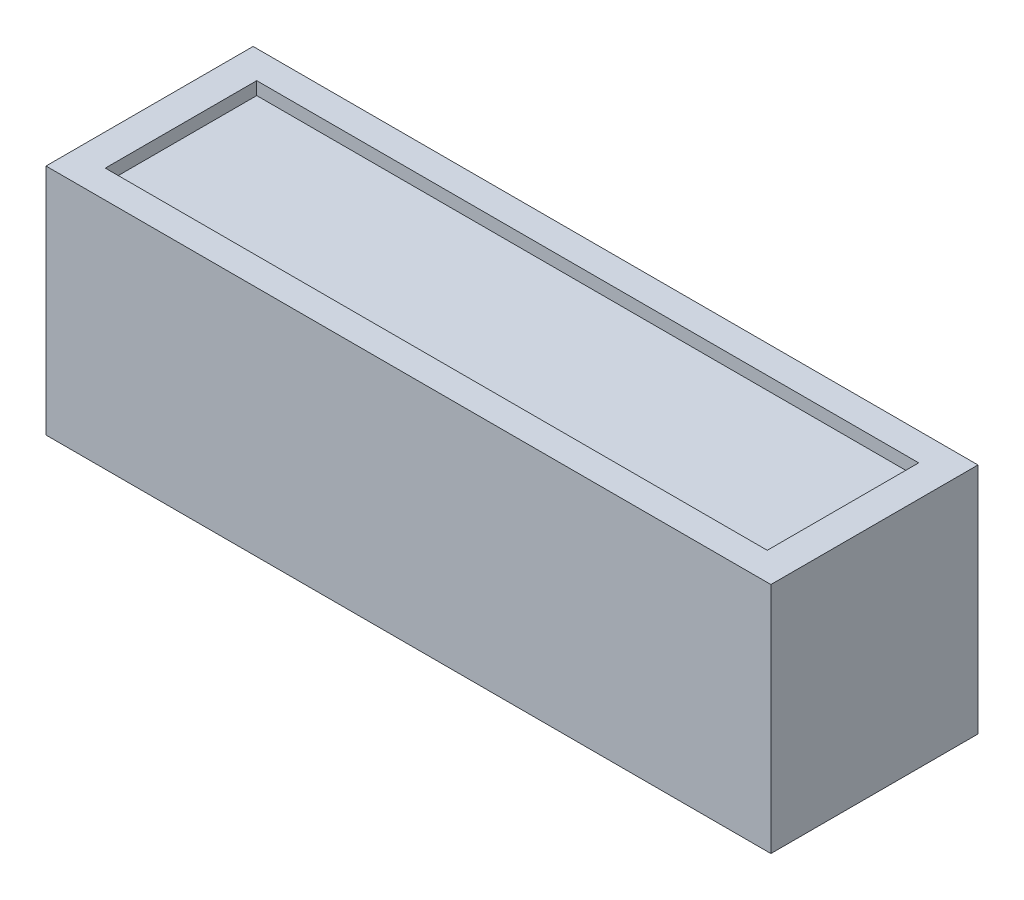
SolidWorks part; units mm, degrees
material "ABS"
ref_plane "Front Plane" through (0, 0, 0) normal (0, 0, 1) x (1, 0, 0)
ref_plane "Top Plane" through (0, 0, 0) normal (0, 1, 0) x (1, 0, 0)
ref_plane "Right Plane" through (0, 0, 0) normal (1, 0, 0) x (0, 0, -1)
sketch "Sketch1" plane through (0, 0, 0) normal (0, 0, 1) x (1, 0, 0)
  line L1 (0, 0) -> (28, 0)
  line L2 (0, 0) -> (0, 9)
  line L3 (0, 9) -> (28, 9)
  line L4 (28, 0) -> (28, 9)
  dimension "D1" = 9
  dimension "D2" = 28
extrude "Boss-Extrude1" add sketch "Sketch1" along normal blind 8
sketch "Sketch2" plane through (0, 9, 0) normal (0, 1, 0) x (1, 0, 0)
  line L0 (14, -1.0749) -> (1.2153, -1.0749)
  line L1 (1.2153, -1.0749) -> (1.2153, -4)
  line L2 (1.2153, -4) -> (1.2153, -6.9251)
  line L3 (1.2153, -6.9251) -> (26.7847, -6.9251)
  line L4 (26.7847, -6.9251) -> (26.7847, -1.0749)
  line L5 (26.7847, -1.0749) -> (14, -1.0749)
  line L6 (14, 0) -> (14, -1.0749) construction
  line L7 (28, 0) -> (0, 0) construction
  line L8 (0, -4) -> (1.2153, -4) construction
  line L9 (0, -8) -> (0, 0) construction
extrude "Cut-Extrude1" cut sketch "Sketch2" against normal blind 0.5
